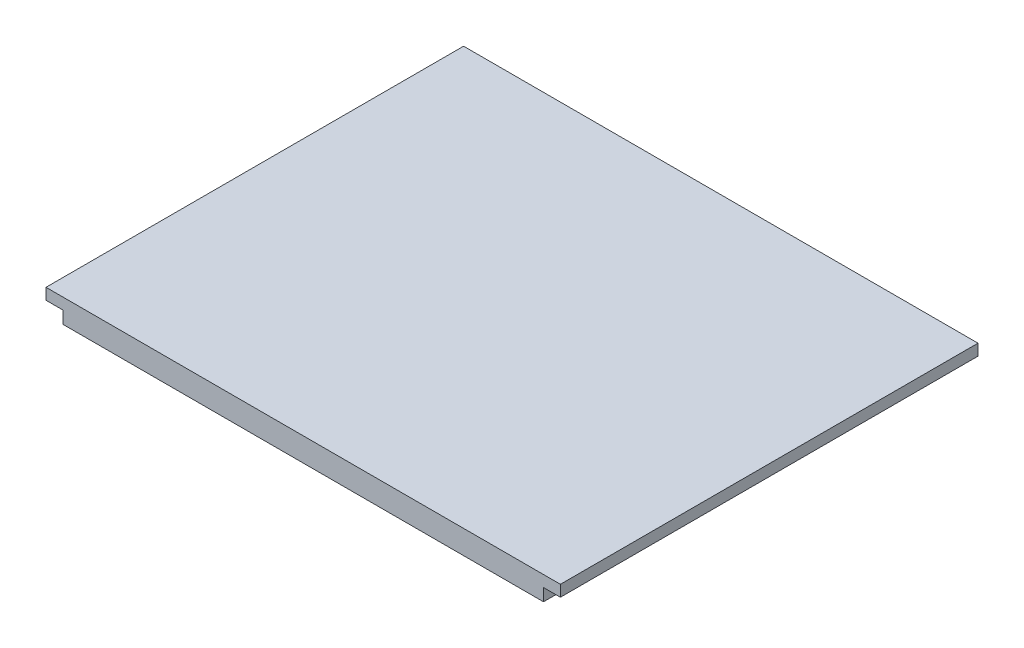
SolidWorks part; units mm, degrees
ref_plane "Front Plane" through (0, 0, 0) normal (0, 0, 1) x (1, 0, 0)
ref_plane "Top Plane" through (0, 0, 0) normal (0, 1, 0) x (1, 0, 0)
ref_plane "Right Plane" through (0, 0, 0) normal (1, 0, 0) x (0, 0, -1)
sketch "Sketch2" plane through (0, 0, 0) normal (0, 0, 1) x (1, 0, 0)
  line L0 (42.7, 0) -> (-42.7, 0)
  line L1 (-42.7, 0) -> (-42.7, 2.2)
  line L2 (-42.7, 2.2) -> (-45.7, 2.2)
  line L3 (-45.7, 2.2) -> (-45.7, 4.2)
  line L4 (-45.7, 4.2) -> (45.7, 4.2)
  line L5 (45.7, 4.2) -> (45.7, 2.2)
  line L6 (45.7, 2.2) -> (42.7, 2.2)
  line L7 (42.7, 2.2) -> (42.7, 0)
  point P0 (0, 4.2)
  point P4 (0, 0)
  dimension "D1" = 2
  dimension "D2" = 91.4
  dimension "D3" = 85.4
  dimension "D4" = 2.2
extrude "Boss-Extrude1" add sketch "Sketch2" along normal blind 74.2
